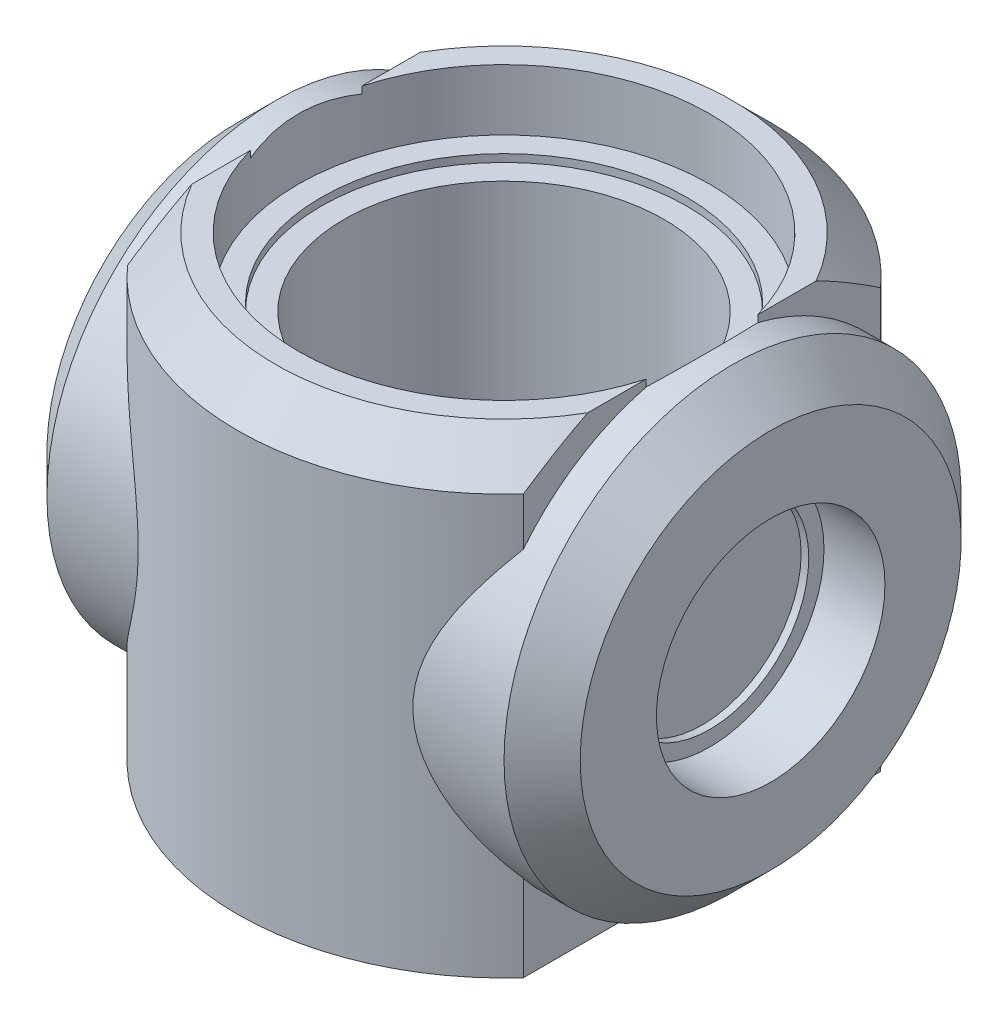
SolidWorks part; units mm, degrees
ref_plane "Front Plane" through (0, 0, 0) normal (0, 0, 1) x (1, 0, 0)
ref_plane "Top Plane" through (0, 0, 0) normal (0, 1, 0) x (1, 0, 0)
ref_plane "Right Plane" through (0, 0, 0) normal (1, 0, 0) x (0, 0, -1)
sketch "Sketch3" plane through (0, 0, 0) normal (0, 1, 0) x (1, 0, 0)
  line L0 (0, 0) -> (-13, 0) construction
  line L1 (-13, 0) -> (-13, 6.5)
  line L2 (-13.5, 7.5) -> (-17.5, 7.5)
  line L3 (-17.5, 7.5) -> (-17.5, 15)
  line L4 (-17.5, 15) -> (0, 15)
  line L5 (0, 15) -> (0, 0)
  line L6 (-13.5, 7.5) -> (-13.5, 6.5)
  line L7 (-13.5, 6.5) -> (-13, 6.5)
  line L8 (0, 0) -> (-13, 0)
  line L9 (-13, 0) -> (-23.8412, 0) construction
  dimension "D1" = 4.5
  dimension "D2" = 0.5
  dimension "D3" = 1
  dimension "D4" = 15
  dimension "D5" = 17.5
  dimension "D6" = 30
revolve "Revolve1" add sketch "Sketch3" angle 360 about L0
mirror "Mirror1" about plane through (0, 0, 0) normal (1, 0, 0) of "Revolve1"
sketch "Sketch6" plane through (0, 0, 0) normal (0, 1, 0) x (1, 0, 0)
  line L0 (-12.9936, 11.7225) -> (-12.9936, -11.7225)
  line L1 (12.9936, 11.7225) -> (12.9936, -11.7225)
  line L2 (-17.4936, 0.4737) -> (-17.4936, 3.9653) construction
  circle A0 centre (0, 0) radius 17.5
  dimension "D1" = 4.5
  dimension "D2" = 35
extrude "Boss-Extrude1" add sketch "Sketch6" against normal mid plane 30 contours L1 A0 L0
sketch "Sketch8" plane through (0, 0, 0) normal (0, 0, 1) x (1, 0, 0)
  line L0 (0, 0) -> (0, -16.9734) construction
  line L1 (0, -15) -> (13.5, -15)
  line L2 (-12.9936, -15) -> (12.9936, -15) construction
  line L3 (13.5, -15) -> (13.5, -11)
  line L4 (13.5, -11) -> (12, -11)
  line L5 (12, -11) -> (12, -10.5)
  line L6 (12, -10.5) -> (10.5, -10.5)
  line L7 (10.5, -10.5) -> (10.5, 10.5)
  line L9 (0, 0) -> (10.5, 0) construction
  line L10 (0, 15) -> (13.5, 15)
  line L11 (13.5, 15) -> (13.5, 11)
  line L12 (13.5, 11) -> (12, 11)
  line L13 (12, 11) -> (12, 10.5)
  line L14 (12, 10.5) -> (10.5, 10.5)
  line L15 (0, 15) -> (0, -15)
  dimension "D1" = 27
  dimension "D2" = 4
  dimension "D3" = 24
  dimension "D4" = 0.5
  dimension "D5" = 21
revolve "Cut-Revolve1" cut sketch "Sketch8" angle 360 about L15
chamfer "2,5mm Chamfer" distance 2.5 angle 45 4 edges at (17.5, 0, -15) (-17.5, 0, -15) (0, 15, 17.5) (0, 15, -17.5)
